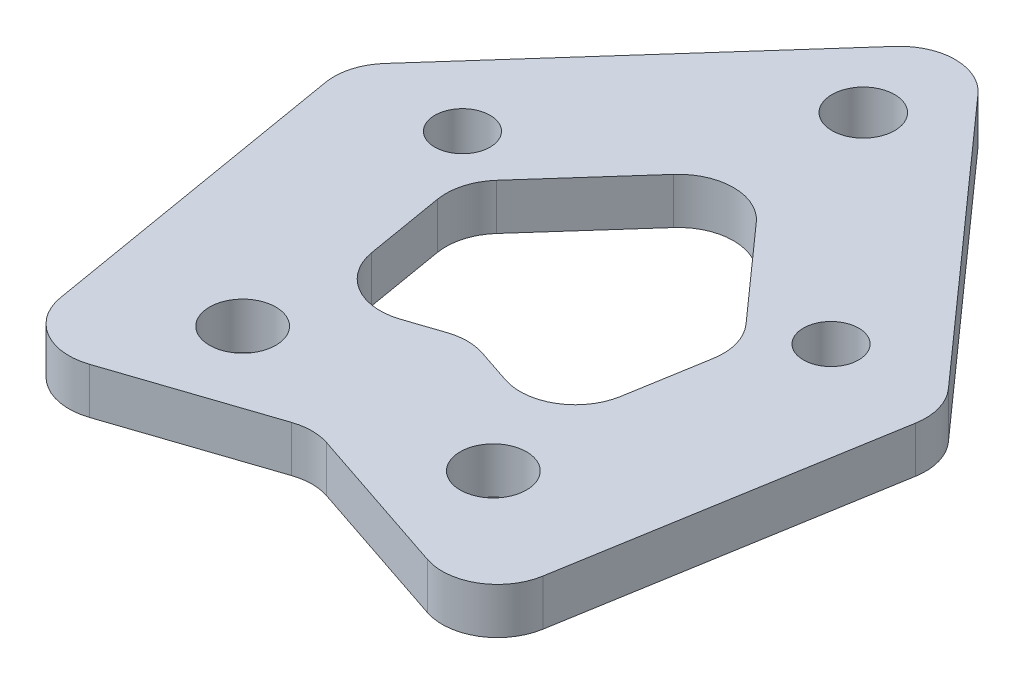
SolidWorks part; units mm, degrees
ref_plane "Front Plane" through (0, 0, 0) normal (0, 0, 1) x (1, 0, 0)
ref_plane "Top Plane" through (0, 0, 0) normal (0, 1, 0) x (1, 0, 0)
ref_plane "Right Plane" through (0, 0, 0) normal (1, 0, 0) x (0, 0, -1)
sketch "Sketch1" plane through (0, 0, 0) normal (0, 1, 0) x (1, 0, 0)
  line L0 (0, 20.0025) -> (64.77, 20.0025) construction
  line L5 (0, 38.0694) -> (0, 1.9356) construction
  line L10 (11.7475, 20.0025) -> (32.385, 43.18)
  line L11 (32.385, 43.18) -> (53.0225, 20.0025)
  line L12 (11.7475, 20.0025) -> (16.51, -8.1728)
  line L13 (64.77, 38.0694) -> (64.77, 1.9356) construction
  line L15 (-77.7875, 40.005) -> (142.5575, 40.005) construction
  line L19 (48.26, -8.1728) -> (53.0225, 20.0025)
  line L22 (16.51, -8.1728) -> (32.385, -2.8575)
  line L23 (32.385, -2.8575) -> (48.26, -8.1728)
  point P6 (0, 0)
  point P8 (32.4838, -2.8575)
  point P17 (41.5827, 43.18)
  point P18 (32.385, 40.005)
  dimension "D1" = 41.275
  dimension "D2" = 31.75
  dimension "D3" = 28.575
  dimension "D4" = 23.1775
  dimension "D5" = 22.86
extrude "Boss-Extrude1" add sketch "Sketch1" along normal mid plane 3.175
sketch "Sketch2" plane through (0, -1.5875, 0) normal (0, 1, 0) x (1, 0, 0)
  line L4 (32.385, 43.18) -> (32.385, 0.8047) construction
  circle A0 centre (19.685, 20.0025) radius 1.905
  circle A1 centre (45.085, 20.0025) radius 1.905
  circle A2 centre (19.685, 20.0025) radius 2.286 construction
  circle A3 centre (45.085, 20.0025) radius 7.239 construction
  circle A5 centre (32.385, 34.925) radius 2.159
  circle A8 centre (23.7475, 0.7955) radius 2.286
  circle A10 centre (41.0225, 0.7955) radius 2.286
  point P9 (32.385, 21.9924)
  point P13 (0, 0)
  point P19 (32.5638, -1.6534)
  point P21 (32.2622, 0.7955)
  point P22 (24.182, 1.8313)
  point P23 (23.7475, 0.3816)
  point P24 (23.7475, -0.0231)
  dimension "D1" = 3.81
  dimension "D2" = 8.6375
  dimension "D7" = 4.318
  dimension "D4" = 21.1968
  dimension "D5" = 4.572
  dimension "D3" = 8.255
extrude "Cut-Extrude1" cut sketch "Sketch2" along normal through all
sketch "Sketch4" plane through (0, 1.5875, 0) normal (0, 1, 0) x (1, 0, 0)
  line L30 (22.5781, 16.8879) -> (24.5481, 5.2329)
  line L31 (24.5481, 5.2329) -> (32.385, 7.8569)
  line L32 (32.385, 7.8569) -> (40.2219, 5.2329)
  line L33 (40.2219, 5.2329) -> (42.1919, 16.8879)
  line L34 (42.1919, 16.8879) -> (32.385, 27.9018)
  line L35 (32.385, 27.9018) -> (22.5781, 16.8879)
  line L36 (22.5781, 16.8879) -> (24.5481, 5.2329)
  line L37 (24.5481, 5.2329) -> (32.385, 7.8569)
  line L38 (32.385, 7.8569) -> (40.2219, 5.2329)
  line L39 (40.2219, 5.2329) -> (42.1919, 16.8879)
  line L40 (42.1919, 16.8879) -> (32.385, 27.9018)
  line L41 (32.385, 27.9018) -> (22.5781, 16.8879)
  dimension "D1" = 10.16
extrude "Cut-Extrude3" cut sketch "Sketch4" against normal through all
fillet "Fillet2" radius 3.81 12 edges at (11.7475, 0, -20.0025) (32.385, 0, -43.18) (53.0225, 0, -20.0025) (32.385, 0, 2.8575) (16.51, 0, 8.1728) (48.26, 0, 8.1728) (42.1919, 0, -16.8879) (40.2219, 0, -5.2329) (32.385, 0, -7.8569) (24.5481, 0, -5.2329) (22.5781, 0, -16.8879) (32.385, 0, -27.9018)
